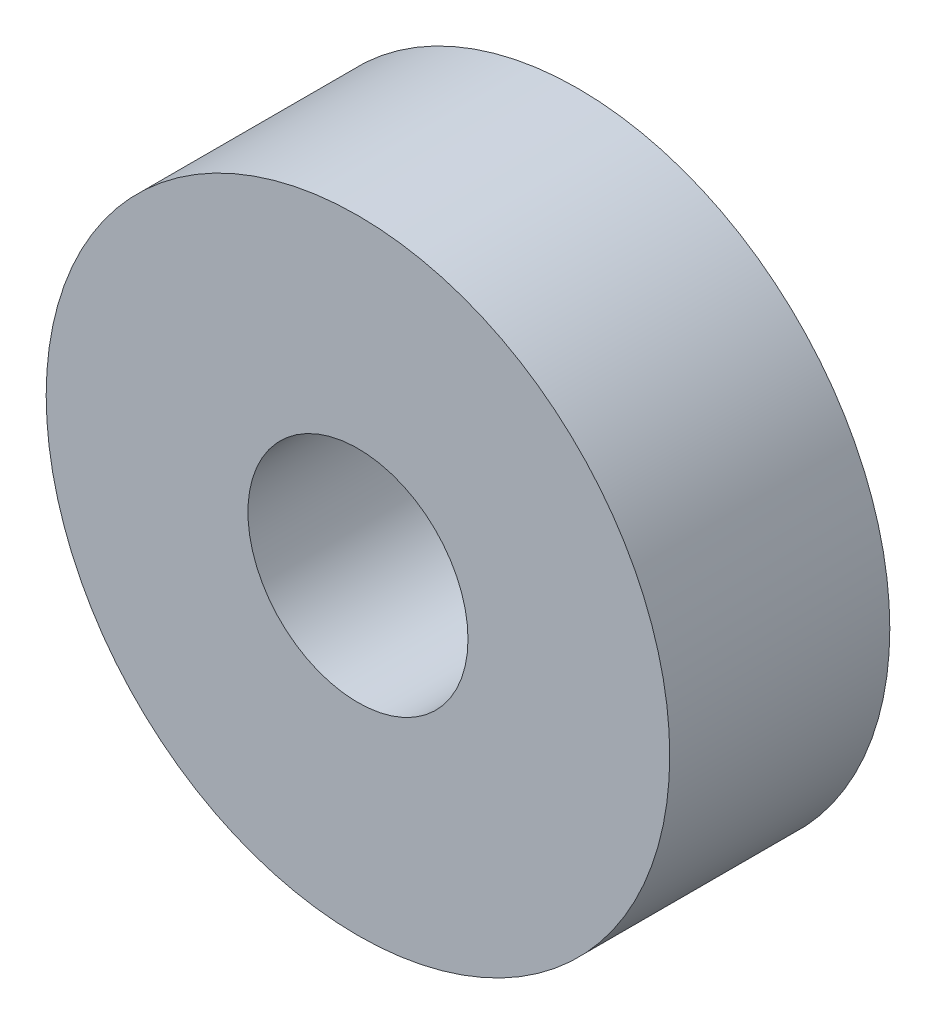
SolidWorks part; units mm, degrees
ref_plane "Front Plane" through (0, 0, 0) normal (0, 0, 1) x (1, 0, 0)
ref_plane "Top Plane" through (0, 0, 0) normal (0, 1, 0) x (1, 0, 0)
ref_plane "Right Plane" through (0, 0, 0) normal (1, 0, 0) x (0, 0, -1)
sketch "Çizim1" plane through (0, 0, 0) normal (0, 0, 1) x (1, 0, 0)
  circle A0 centre (0, 0) radius 8.5
  circle A1 centre (0, 0) radius 3
  dimension "D1" = 17
  dimension "D2" = 6
extrude "Yükseklik-Ekstrüzyon1" add sketch "Çizim1" along normal blind 6
